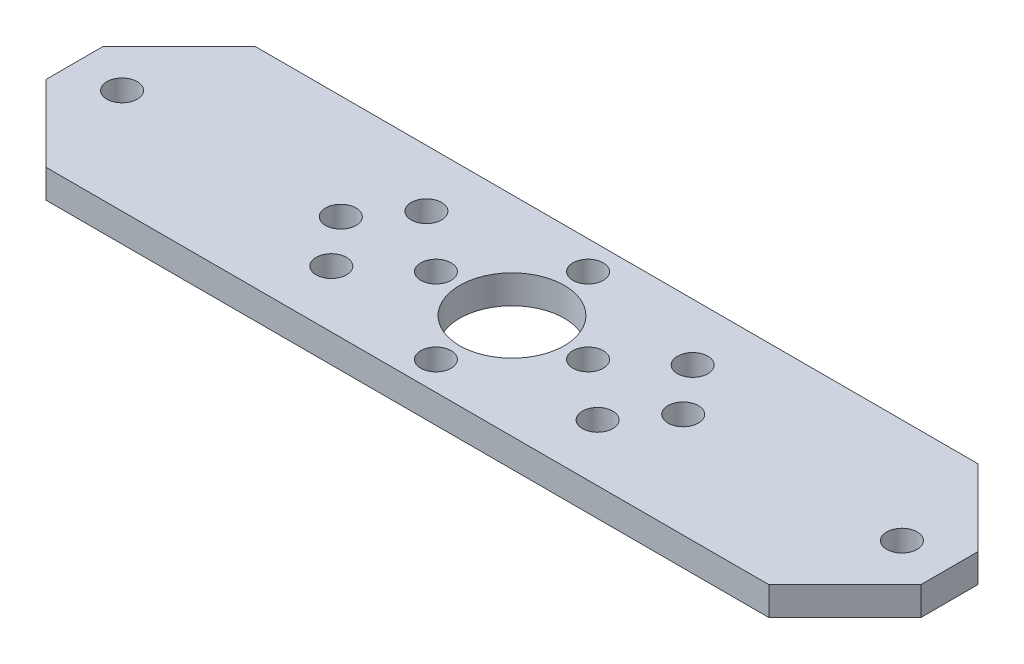
SolidWorks part; units mm, degrees
material "玻"
ref_plane "前视基准面" through (0, 0, 0) normal (0, 0, 1) x (1, 0, 0)
ref_plane "上视基准面" through (0, 0, 0) normal (0, 1, 0) x (1, 0, 0)
ref_plane "右视基准面" through (0, 0, 0) normal (1, 0, 0) x (0, 0, -1)
sketch "草图1" plane through (0, 0, 0) normal (0, 1, 0) x (1, 0, 0)
  line L0 (0, 0) -> (25.2004, 0) construction
  line L1 (0, 0) -> (0, 32.3199) construction
  line L7 (-46, 3) -> (-38, 11)
  line L8 (-38, -11) -> (38, -11)
  line L9 (-46, -3) -> (-46, 3)
  line L10 (-38, 11) -> (38, 11)
  line L11 (46, -3) -> (46, 3)
  line L12 (-46, -11) -> (46, 11) construction
  line L13 (-46, 11) -> (46, -11) construction
  line L14 (-46, -3) -> (-38, -11)
  line L15 (38, -11) -> (46, -3)
  line L16 (38, 11) -> (46, 3)
  circle A0 centre (0, 0) radius 11 construction
  circle A1 centre (0, 8) radius 1.6
  circle A3 centre (8, 0) radius 1.6
  circle A4 centre (-8, 0) radius 1.6
  circle A15 centre (0, 0) radius 5.5
  circle A16 centre (0, -8) radius 1.6
  circle A17 centre (-18, 0) radius 1.6
  circle A18 centre (-14, 5) radius 1.6
  circle A19 centre (-14, -5) radius 1.6
  circle A20 centre (14, -5) radius 1.6
  circle A21 centre (18, 0) radius 1.6
  circle A22 centre (14, 5) radius 1.6
  circle A23 centre (-41, 0) radius 1.6
  circle A24 centre (41, 0) radius 1.6
  dimension "D2" = 3.2
  dimension "D3" = 8
  dimension "D4" = 3.2
  dimension "D5" = 8
  dimension "D8" = 92
  dimension "D9" = 3.2
  dimension "D10" = 28
  dimension "D14" = 11
  dimension "D15" = 11
  dimension "D16" = 3.2
  dimension "D6" = 22
  dimension "D17" = 32
  dimension "D18" = 6
  dimension "D19" = 3.2
  dimension "D20" = 11
  dimension "D21" = 5
  dimension "D7" = 22
extrude "凸台-拉伸1" add sketch "草图1" along normal blind 3
